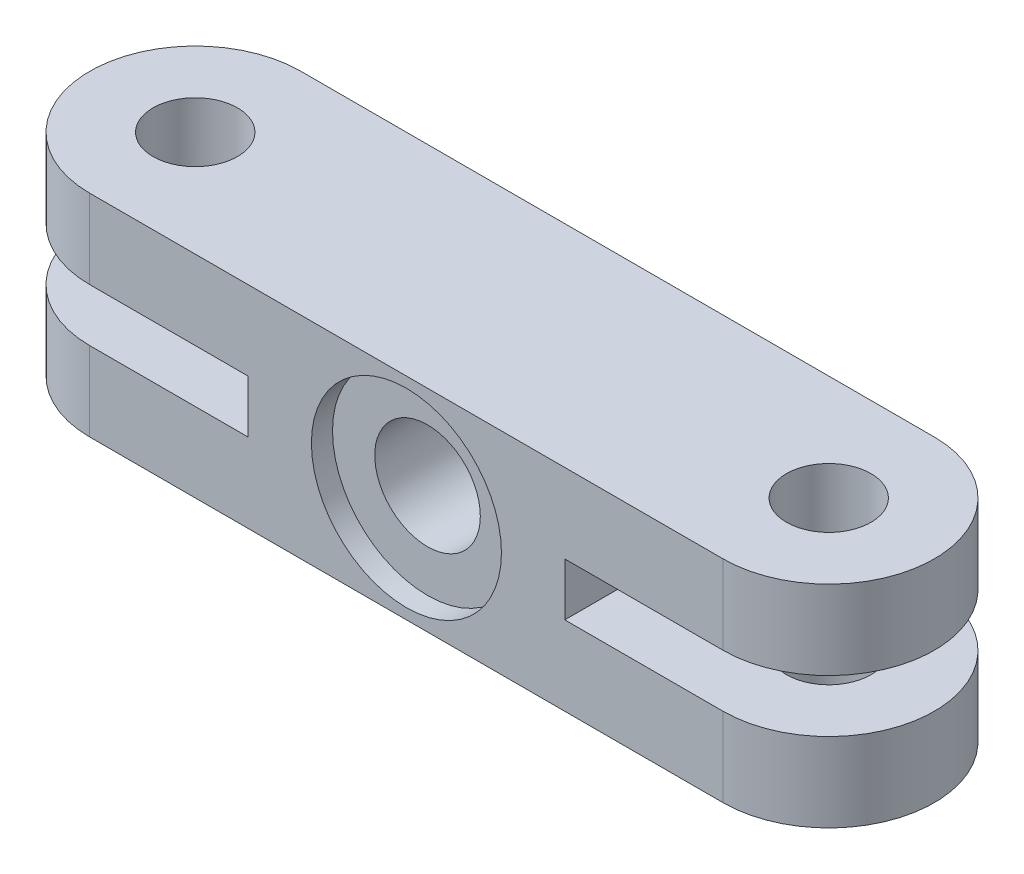
SolidWorks part; units mm, degrees
ref_plane "Front Plane" through (0, 0, 0) normal (0, 0, 1) x (1, 0, 0)
ref_plane "Top Plane" through (0, 0, 0) normal (0, 1, 0) x (1, 0, 0)
ref_plane "Right Plane" through (0, 0, 0) normal (1, 0, 0) x (0, 0, -1)
sketch "Sketch1" plane through (0, 0, 0) normal (0, 1, 0) x (1, 0, 0)
  line L0 (-30, 0) -> (30, 0) construction
  line L1 (-30, 10) -> (30, 10)
  line L2 (-30, -10) -> (30, -10)
  arc A0 (-30, 10) -> (-30, -10) centre (-30, 0) ccw
  arc A1 (30, -10) -> (30, 10) centre (30, 0) ccw
  circle A2 centre (-30, 0) radius 4
  circle A3 centre (30, 0) radius 4
  point P3 (0, 0)
  point P12 (0, 0)
  dimension "D1" = 10
  dimension "D3" = 8
  dimension "D2" = 60
extrude "Boss-Extrude1" add sketch "Sketch1" along normal mid plane 20
sketch "Sketch3" plane through (0, 0, 10) normal (0, 0, 1) x (1, 0, 0)
  line L0 (0, 0) -> (0, 16.8796) construction
  line L1 (40, 2.5) -> (15, 2.5)
  line L3 (40, -2.5) -> (15, -2.5)
  line L4 (15, 2.5) -> (15, -2.5)
  line L5 (-40, 2.5) -> (-40, -2.5)
  line L6 (-40, 2.5) -> (-15, 2.5)
  line L7 (40, 2.5) -> (40, -2.5)
  line L8 (-15, 2.5) -> (-15, -2.5)
  line L9 (-40, -2.5) -> (-15, -2.5)
  dimension "D1" = 25
  dimension "D2" = 5
extrude "Cut-Extrude1" cut sketch "Sketch3" against normal through all
hole_wizard "Hole1" positions "Sketch4" profile "Sketch5" legacy end condition through all
sketch "Sketch4" plane through (0, 0, 10) normal (0, 0, 1) x (1, 0, 0)
  point P0 (0, 0)
sketch "Sketch5" plane through (0, 0, 10) normal (1, 0, 0) x (0, -1, 0)
  line L0 (0, 0) -> (0, 20)
  line L1 (0, 20) -> (5, 20)
  line L2 (5, 20) -> (5, 2)
  line L3 (5, 2) -> (9, 2)
  line L4 (9, 2) -> (9, 0)
  line L5 (9, 0) -> (0, 0)
  line L6 (0, 110) -> (0, -10) construction
  dimension "Diameter" = 10
  dimension "Depth" = 20
  dimension "C-Bore Diameter" = 18
  dimension "C-Bore Depth" = 2
